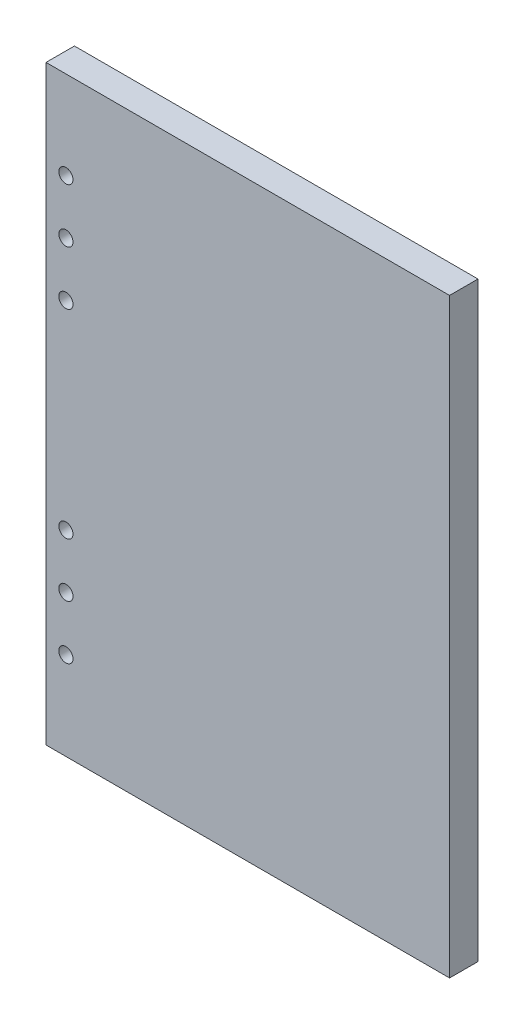
SolidWorks part; units mm, degrees
ref_plane "Спереди" through (0, 0, 0) normal (0, 0, 1) x (1, 0, 0)
ref_plane "Сверху" through (0, 0, 0) normal (0, 1, 0) x (1, 0, 0)
ref_plane "Справа" through (0, 0, 0) normal (1, 0, 0) x (0, 0, -1)
sketch "Эскиз1" plane through (0, 0, 0) normal (0, 0, 1) x (1, 0, 0)
  line L0 (0, 104) -> (142, 104) construction
  line L1 (0, 0) -> (142, 0)
  line L2 (0, 0) -> (0, 208)
  line L3 (0, 208) -> (142, 208)
  line L4 (142, 0) -> (142, 208)
  line L5 (7, 104) -> (7, 139) construction
  line L6 (7, 177) -> (7, 158) construction
  line L7 (7, 158) -> (7, 139) construction
  line L8 (7, 50) -> (7, 69) construction
  line L9 (7, 31) -> (7, 50) construction
  circle A0 centre (7, 139) radius 2.5
  circle A1 centre (7, 158) radius 2.5
  circle A2 centre (7, 177) radius 2.5
  circle A3 centre (7, 31) radius 2.5
  circle A4 centre (7, 50) radius 2.5
  circle A5 centre (7, 69) radius 2.5
  dimension "D3" = 5
  dimension "D4" = 5
  dimension "D5" = 5
  dimension "D6" = 19
  dimension "D7" = 19
  dimension "D8" = 70
  dimension "D1" = 142
  dimension "D2" = 208
  dimension "D9" = 7
extrude "Бобышка-Вытянуть1" add sketch "Эскиз1" along normal blind 10
